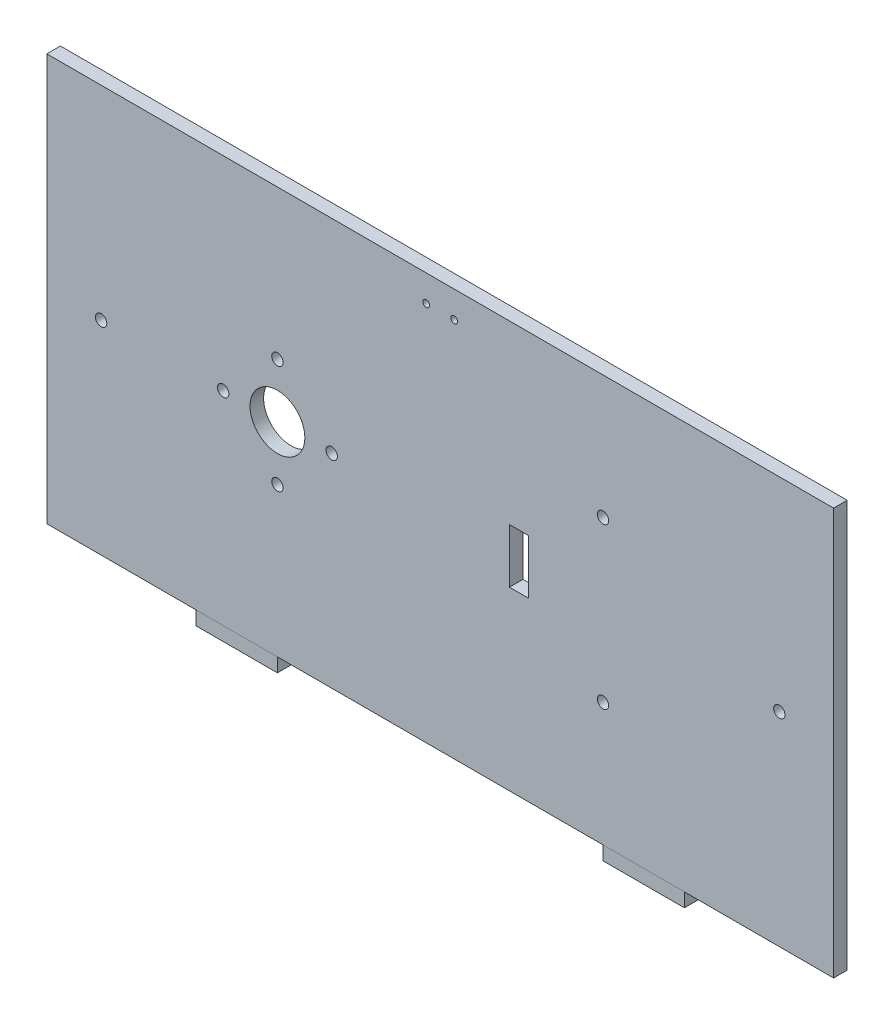
SolidWorks part; units mm, degrees
ref_plane "Front Plane" through (0, 0, 0) normal (0, 0, 1) x (1, 0, 0)
ref_plane "Top Plane" through (0, 0, 0) normal (0, 1, 0) x (1, 0, 0)
ref_plane "Right Plane" through (0, 0, 0) normal (1, 0, 0) x (0, 0, -1)
sketch "Sketch1" plane through (0, 0, 0) normal (0, 0, 1) x (1, 0, 0)
  line L1 (-145, 75) -> (145, 75)
  line L2 (-145, 75) -> (-145, -75)
  line L3 (-145, -75) -> (145, -75)
  line L4 (145, 75) -> (145, -75)
  line L5 (-145, 75) -> (145, -75) construction
  line L6 (-145, -75) -> (145, 75) construction
  point P0 (0, 0)
  dimension "D1" = 290
  dimension "D2" = 150
extrude "Boss-Extrude1" add sketch "Sketch1" along normal blind 5
sketch "Sketch2" plane through (0, 0, 5) normal (0, 0, 1) x (1, 0, 0)
  line L0 (-147.5, 65.2) -> (147.5, 65.2) construction
  line L3 (145, 75) -> (-145, 75) construction
  line L4 (0, 65.2) -> (-5.15, 65.2)
  line L5 (0, 65.2) -> (5.15, 65.2)
  circle A0 centre (-5.15, 65.2) radius 1.25
  circle A1 centre (5.15, 65.2) radius 1.25
  dimension "D2" = 5.15
  dimension "D3" = 2.5
  dimension "D4" = 2.5
  dimension "D1" = 9.8
  dimension "D5" = 5.15
extrude "Cut-Extrude1" cut sketch "Sketch2" against normal blind 5 contours A0 L0 L4 | L0 A0 L4 | L5 L0 A1 | L0 L5 A1
sketch "Sketch3" plane through (0, 0, 5) normal (0, 0, 1) x (1, 0, 0)
  line L0 (0, -75) -> (-145, -75)
  line L2 (-145, -75) -> (145, -75) construction
  line L3 (0, -75) -> (145, -75)
  line L4 (-90, -69.9) -> (-60, -69.9)
  line L5 (-90, -69.9) -> (-90, -80.1)
  line L6 (-90, -80.1) -> (-60, -80.1)
  line L7 (-60, -69.9) -> (-60, -80.1)
  line L8 (-90, -69.9) -> (-60, -80.1) construction
  line L9 (-90, -80.1) -> (-60, -69.9) construction
  line L10 (60, -69.9) -> (90, -69.9)
  line L11 (60, -69.9) -> (60, -80.1)
  line L12 (60, -80.1) -> (90, -80.1)
  line L13 (90, -69.9) -> (90, -80.1)
  line L14 (60, -69.9) -> (90, -80.1) construction
  line L15 (60, -80.1) -> (90, -69.9) construction
  point P5 (-75, -75)
  point P12 (75, -75)
  dimension "D1" = 30
  dimension "D2" = 30
  dimension "D3" = 10.2
  dimension "D4" = 10.2
  dimension "D5" = 75
  dimension "D6" = 75
extrude "Boss-Extrude2" add sketch "Sketch3" against normal blind 5 separate body contours L7 L0 L5 L6 | L13 L3 L11 L12
sketch "Sketch4" plane through (0, 0, 0) normal (0, 0, -1) x (-1, 0, 0)
  line L0 (-145, -75) -> (-145, 75) construction
  line L1 (-145, 75) -> (145, 75) construction
  line L2 (0, 75) -> (0, -75) construction
  line L3 (145, -75) -> (-145, -75) construction
  circle A0 centre (-125, 0) radius 2.1
  circle A1 centre (125, 0) radius 2.1
  dimension "D3" = 4.2
  dimension "D1" = 20
  dimension "D2" = 75
extrude "Cut-Extrude2" cut sketch "Sketch4" against normal blind 10
sketch "Sketch5" plane through (0, 0, 0) normal (0, 0, -1) x (-1, 0, 0)
  line L0 (145, 0) -> (60, 0) construction
  line L1 (145, 75) -> (145, -75) construction
  circle A0 centre (60, 0) radius 10.1
  dimension "D1" = 85
extrude "Cut-Extrude3" cut sketch "Sketch5" against normal blind 10
sketch "Sketch6" plane through (0, 0, 0) normal (0, 0, -1) x (-1, 0, 0)
  line L0 (-145, 0) -> (145, 0) construction
  line L1 (-145, -75) -> (-145, 75) construction
  line L2 (145, 75) -> (145, -75) construction
  circle A0 centre (-60, 29.5) radius 2.1
  circle A1 centre (-60, -29.5) radius 2.1
  dimension "D1" = 4.2
  dimension "D4" = 4.2
  dimension "D2" = 29.5
  dimension "D3" = 29.5
  dimension "D5" = 85
  dimension "D6" = 85
extrude "Cut-Extrude4" cut sketch "Sketch6" against normal blind 10
sketch "Sketch7" plane through (0, 0, 0) normal (0, 0, -1) x (-1, 0, 0)
  circle A0 centre (60, 0) radius 20 construction
  circle A1 centre (60, 20) radius 2.1
  circle A2 centre (80, 0) radius 2.1
  circle A3 centre (60, -20) radius 2.1
  circle A4 centre (40, 0) radius 2.1
  dimension "D1" = 40
  dimension "D2" = 4.2
  dimension "D3" = 4.2
  dimension "D4" = 4.2
  dimension "D5" = 4.2
extrude "Cut-Extrude5" cut sketch "Sketch7" against normal blind 10
sketch "Sketch8" plane through (0, 0, 0) normal (0, 0, -1) x (-1, 0, 0)
  line L0 (0, 0) -> (-29, 0) construction
  line L1 (-32.5, 10) -> (-25.5, 10)
  line L2 (-32.5, 10) -> (-32.5, -10)
  line L3 (-32.5, -10) -> (-25.5, -10)
  line L4 (-25.5, 10) -> (-25.5, -10)
  line L5 (-32.5, 10) -> (-25.5, -10) construction
  line L6 (-32.5, -10) -> (-25.5, 10) construction
  line L7 (60, 0) -> (-29, 0) construction
  point P0 (-29, 0)
  dimension "D1" = 7
  dimension "D2" = 20
  dimension "D3" = 89
extrude "Cut-Extrude6" cut sketch "Sketch8" against normal blind 10
